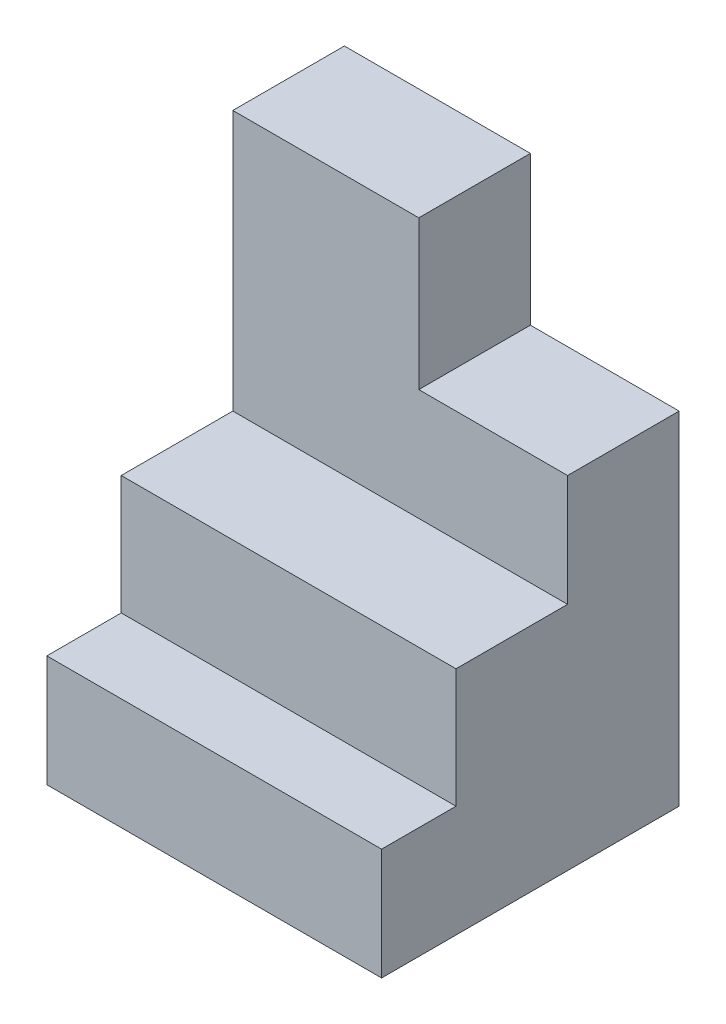
SolidWorks part; units mm, degrees
ref_plane "Plano frontal" through (0, 0, 0) normal (0, 0, 1) x (1, 0, 0)
ref_plane "Plano superior" through (0, 0, 0) normal (0, 1, 0) x (1, 0, 0)
ref_plane "Plano direito" through (0, 0, 0) normal (1, 0, 0) x (0, 0, -1)
sketch "Esboço1" plane through (0, 0, 0) normal (0, 0, 1) x (1, 0, 0)
  line L1 (-1.125, -1.65) -> (1.125, -1.65)
  line L2 (-1.125, -1.65) -> (-1.125, 1.65)
  line L3 (-1.125, 1.65) -> (0.125, 1.65)
  line L4 (1.125, -1.65) -> (1.125, 0.65)
  line L5 (-1.125, -1.65) -> (1.125, 1.65) construction
  line L6 (-1.125, 1.65) -> (1.125, -1.65) construction
  line L9 (1.125, 0.65) -> (0.125, 0.65)
  line L10 (0.125, 1.65) -> (0.125, 0.65)
  point P0 (0, 0)
  dimension "D1" = 3.3
  dimension "D2" = 2.25
  dimension "D3" = 1
  dimension "D4" = 1
extrude "Ressalto-extrusão1" add sketch "Esboço1" along normal blind 0.75
sketch "Esboço2" plane through (0, 0, 0.75) normal (0, 0, 1) x (1, 0, 0)
  line L0 (1.125, -1.65) -> (1.125, 0.65) construction
  line L1 (-1.125, -1.65) -> (1.125, -1.65)
  line L2 (-1.125, -1.65) -> (-1.125, -0.1)
  line L3 (-1.125, -0.1) -> (1.125, -0.1)
  line L4 (1.125, -1.65) -> (1.125, -0.1)
  line L5 (0.125, 1.65) -> (-1.125, 1.65) construction
  dimension "D1" = 1.75
extrude "Ressalto-extrusão2" add sketch "Esboço2" along normal blind 1.25
sketch "Esboço4" plane through (-1.125, 0, 0) normal (-1, 0, 0) x (0, 0, 1)
  line L1 (2, -0.1) -> (1.5, -0.1)
  line L2 (2, -0.1) -> (2, -0.9)
  line L3 (2, -0.9) -> (1.5, -0.9)
  line L4 (1.5, -0.1) -> (1.5, -0.9)
  dimension "D1" = 0.5
  dimension "D2" = 0.8
extrude "Corte-extrusão1" cut sketch "Esboço4" against normal through all
